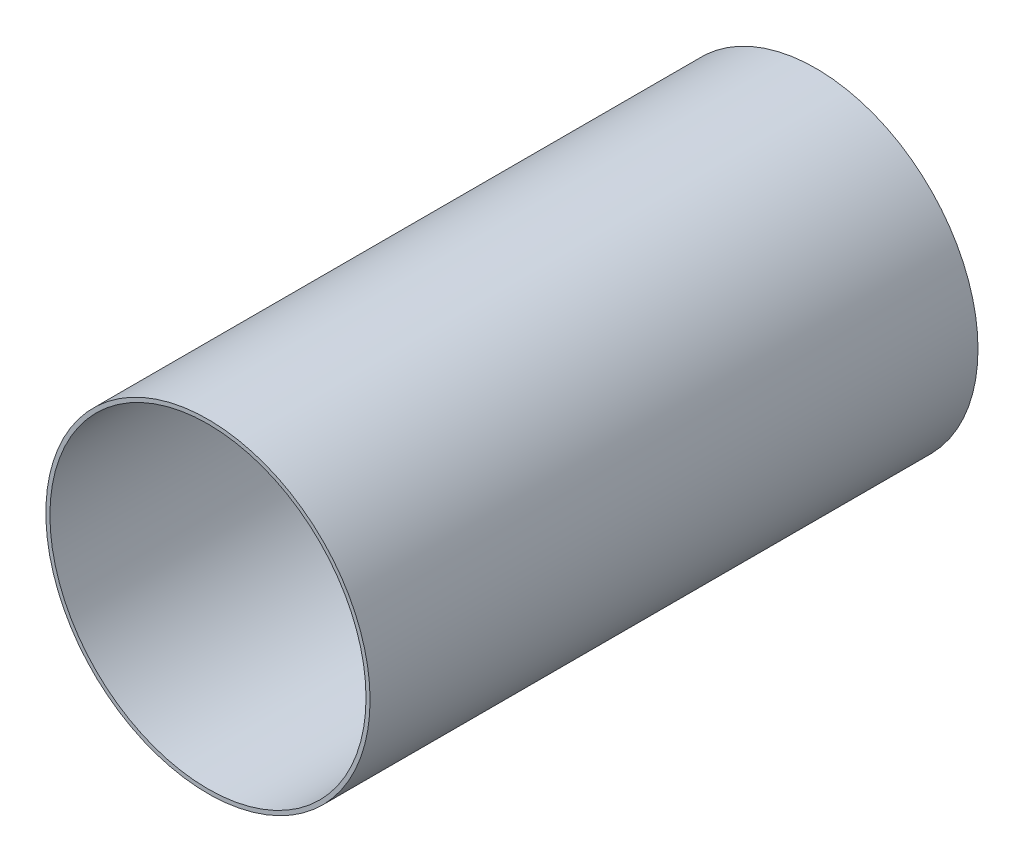
SolidWorks part; units mm, degrees
material "PVC Rigid"
ref_plane "Front Plane" through (0, 0, 0) normal (0, 0, 1) x (1, 0, 0)
ref_plane "Top Plane" through (0, 0, 0) normal (0, 1, 0) x (1, 0, 0)
ref_plane "Right Plane" through (0, 0, 0) normal (1, 0, 0) x (0, 0, -1)
sketch "Sketch1" plane through (0, 0, 0) normal (0, 0, 1) x (1, 0, 0)
  circle A0 centre (0, 0) radius 80
  circle A1 centre (0, 0) radius 78
  dimension "D1" = 160
  dimension "D2" = 2
extrude "Boss-Extrude1" add sketch "Sketch1" along normal blind 300
ref_plane "Plane1" through (0, 0, 150) normal (0, 0, 1) x (1, 0, 0)
